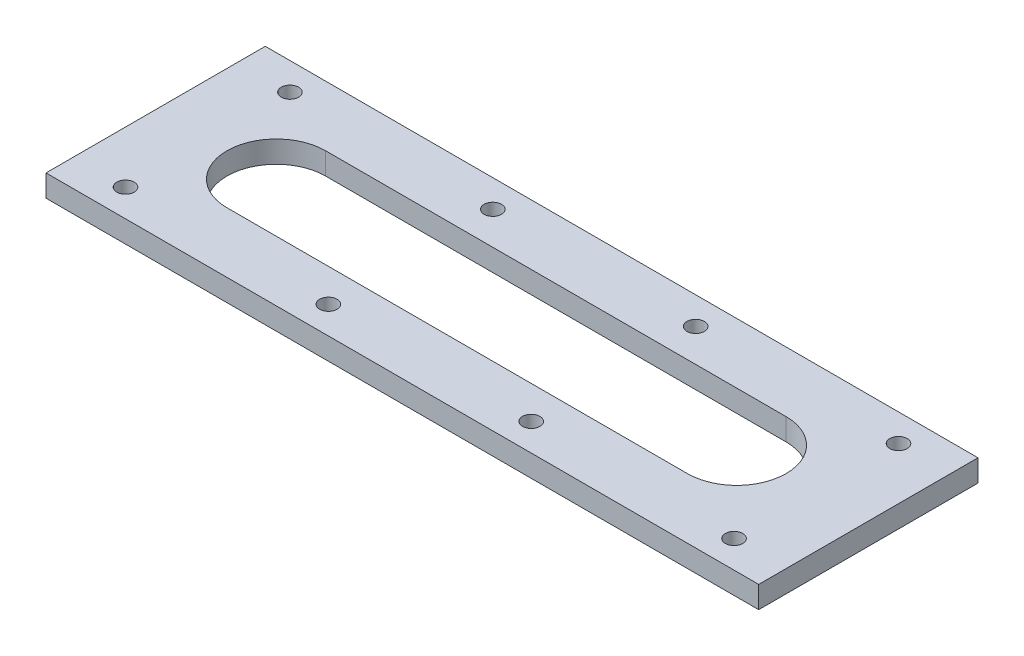
SolidWorks part; units mm, degrees
material "AISI Aço-ferramenta tipo A2"
ref_plane "Plano frontal" through (0, 0, 0) normal (0, 0, 1) x (1, 0, 0)
ref_plane "Plano superior" through (0, 0, 0) normal (0, 1, 0) x (1, 0, 0)
ref_plane "Plano direito" through (0, 0, 0) normal (1, 0, 0) x (0, 0, -1)
sketch "Esboço1" plane through (0, 0, 0) normal (0, 1, 0) x (1, 0, 0)
  line L0 (22, 20) -> (106, 20) construction
  line L1 (0, 0) -> (130, 0)
  line L2 (0, 0) -> (0, 40)
  line L3 (0, 40) -> (130, 40)
  line L4 (130, 0) -> (130, 40)
  line L5 (22, 29) -> (106, 29)
  line L6 (22, 11) -> (106, 11)
  arc A0 (22, 29) -> (22, 11) centre (22, 20) ccw
  arc A1 (106, 11) -> (106, 29) centre (106, 20) ccw
  point P7 (64, 20)
  point P12 (0, 20)
  dimension "D5" = 9
  dimension "D1" = 130
  dimension "D2" = 40
  dimension "D3" = 84
  dimension "D4" = 22
  dimension "D6" = 20
extrude "Ressalto-extrusão1" add sketch "Esboço1" along normal blind 4
sketch "Esboço2" plane through (0, 0, 0) normal (0, -1, 0) x (1, 0, 0)
  line L0 (0, -40) -> (0, 0) construction
  line L2 (130, -40) -> (0, -40) construction
  point P0 (9.5, -35)
  dimension "D1" = 9.5
  dimension "D2" = 5
hole_wizard "Escareado para parafuso com cabeça escareada elevada de M31" positions "Esboço3" profile "Esboço4" countersink size "M3" standard "DIN"
sketch "Esboço3" plane through (0, 0, 0) normal (0, -1, 0) x (-1, 0, 0)
  point P0 (-9.5, 35)
sketch "Esboço4" plane through (9.5, 0, -35) normal (1, 0, 0) x (0, 0, -1)
  line L0 (0, 0) -> (0, 13.9539)
  line L1 (0, 13.9539) -> (1.5875, 13)
  line L2 (1.5875, 13) -> (1.5875, 1.5625)
  line L3 (1.5875, 1.5625) -> (3.15, 0)
  line L5 (3.15, 0) -> (0, 0)
  line L6 (-1.5875, 1.5625) -> (-3.15, 0) construction
  line L10 (0, 13.9539) -> (-1.5875, 13) construction
  line L11 (0, -6.35) -> (0, 107.95) construction
  dimension "Hole Dia." = 3.175
  dimension "Hole Depth" = 13
  dimension "Near C'Sink Dia." = 6.3
  dimension "Near C'Sink Angle" = 90
  dimension "Drill Angle" = 118
pattern_linear "Padrão linear1" count 4 spacing 37 along (1, 0, 0) count 2 spacing 30 along (0, 0, 1) of "Escareado para parafuso com cabeça escareada elevada de M31"
